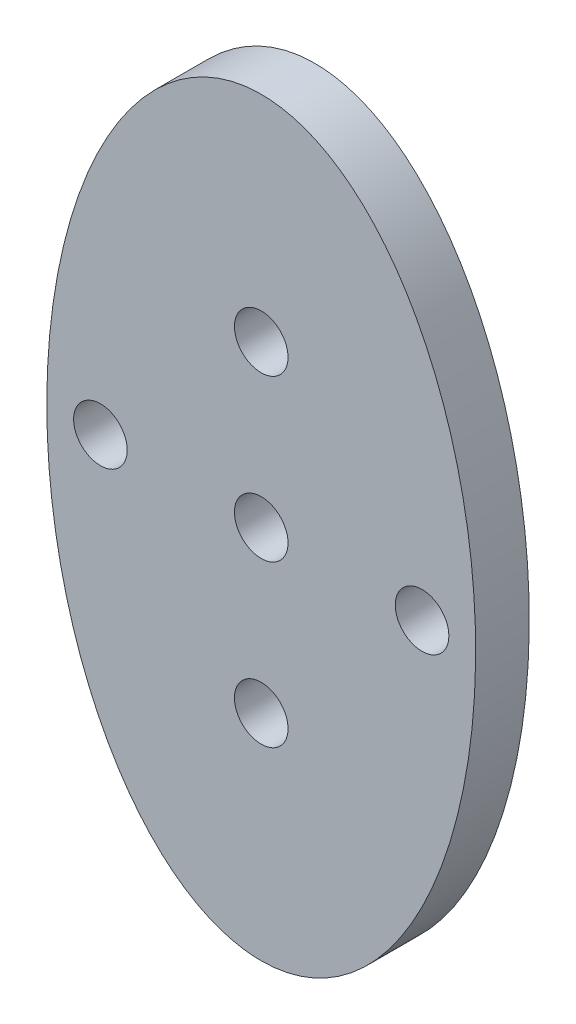
SolidWorks part; units mm, degrees
ref_plane "Alzado" through (0, 0, 0) normal (0, 0, 1) x (1, 0, 0)
ref_plane "Planta" through (0, 0, 0) normal (0, 1, 0) x (1, 0, 0)
ref_plane "Vista lateral" through (0, 0, 0) normal (1, 0, 0) x (0, 0, -1)
sketch "Model" plane through (0, 0, 0) normal (0, 0, 1) x (1, 0, 0)
  circle A0 centre (299.5188, 276.8788) radius 1.5
  circle A1 centre (299.5188, 294.8788) radius 1.5
  circle A2 centre (308.5188, 285.8788) radius 1.5
  circle A3 centre (290.5188, 285.8788) radius 1.5
  circle A4 centre (299.5188, 285.8788) radius 1.5
  ellipse E0 centre (299.5188, 285.8788) end of major axis (299.5188, 264.8788) minor radius 12
extrude "Saliente-Extruir1" add sketch "Model" along normal blind 3
